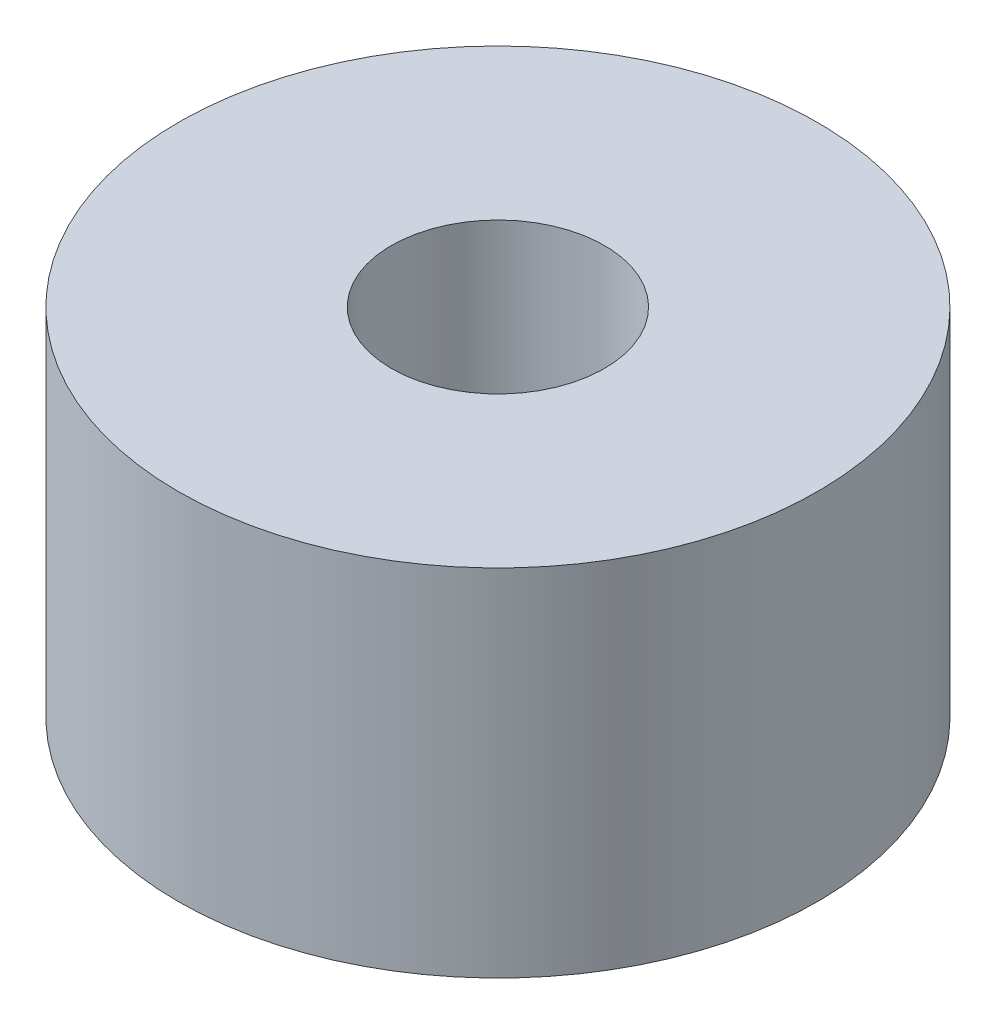
SolidWorks part; units mm, degrees
ref_plane "Front Plane" through (0, 0, 0) normal (0, 0, 1) x (1, 0, 0)
ref_plane "Top Plane" through (0, 0, 0) normal (0, 1, 0) x (1, 0, 0)
ref_plane "Right Plane" through (0, 0, 0) normal (1, 0, 0) x (0, 0, -1)
sketch "Sketch1" plane through (0, 0, 0) normal (0, 1, 0) x (1, 0, 0)
  circle A0 centre (0, 0) radius 4.5
  circle A1 centre (0, 0) radius 1.5
  dimension "D1" = 9
  dimension "D2" = 3
extrude "Boss-Extrude1" add sketch "Sketch1" along normal blind 5
